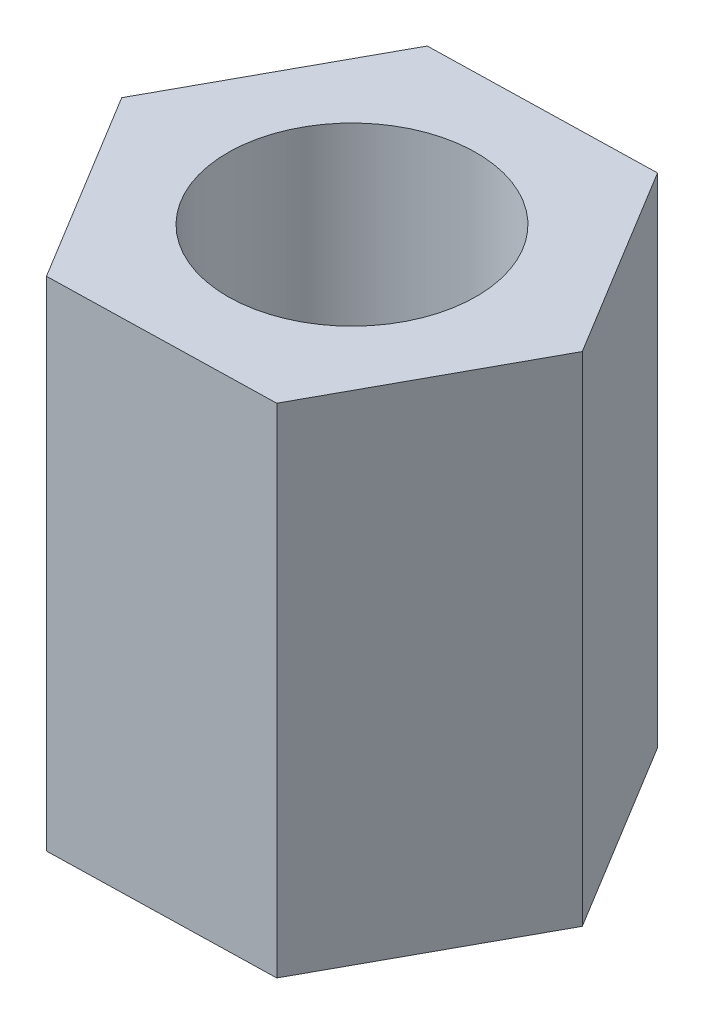
SolidWorks part; units mm, degrees
material "黄铜"
ref_plane "前视基准面" through (0, 0, 0) normal (0, 0, 1) x (1, 0, 0)
ref_plane "上视基准面" through (0, 0, 0) normal (0, 1, 0) x (1, 0, 0)
ref_plane "右视基准面" through (0, 0, 0) normal (1, 0, 0) x (0, 0, -1)
sketch "草图1" plane through (0, 0, 0) normal (0, 1, 0) x (1, 0, 0)
  line L1 (1.4109, -2.3179) -> (2.7128, 0.0629)
  line L2 (2.7128, 0.0629) -> (1.3019, 2.3808)
  line L3 (1.3019, 2.3808) -> (-1.4109, 2.3179)
  line L4 (-1.4109, 2.3179) -> (-2.7128, -0.0629)
  line L5 (-2.7128, -0.0629) -> (-1.3019, -2.3808)
  line L6 (-1.3019, -2.3808) -> (1.4109, -2.3179)
  circle A0 centre (0, 0) radius 2.35 construction
  circle A1 centre (0, 0) radius 1.5
  dimension "D1" = 3
  dimension "D2" = 4.7
extrude "凸台-拉伸1" add sketch "草图1" along normal blind 6
